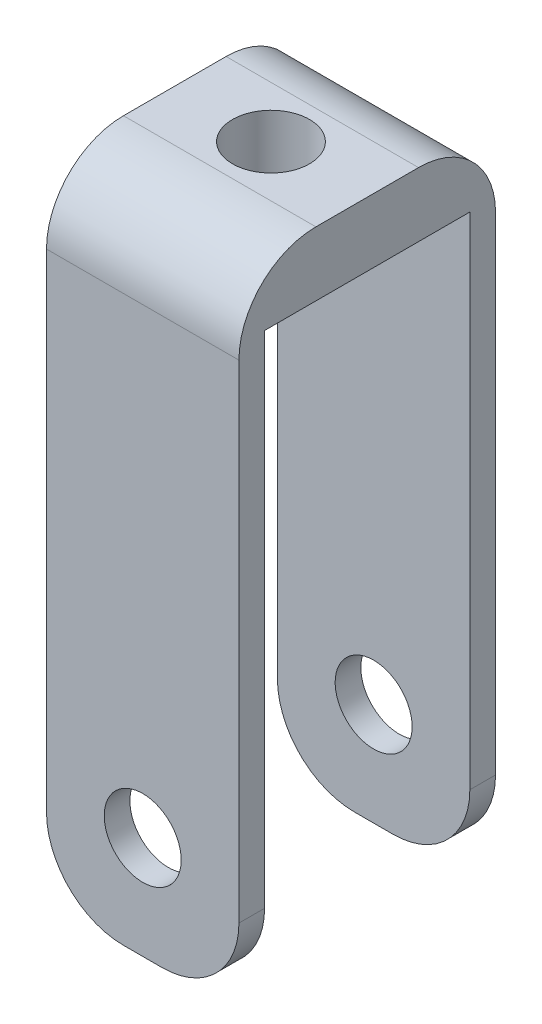
SolidWorks part; units mm, degrees
ref_plane "Front Plane" through (0, 0, 0) normal (0, 0, 1) x (1, 0, 0)
ref_plane "Top Plane" through (0, 0, 0) normal (0, 1, 0) x (1, 0, 0)
ref_plane "Right Plane" through (0, 0, 0) normal (1, 0, 0) x (0, 0, -1)
sketch "Sketch1" plane through (0, 0, 0) normal (1, 0, 0) x (0, 0, -1)
  line L0 (0, 0) -> (-10, 0)
  line L1 (-10, 0) -> (-10, -50)
  line L2 (-10, -50) -> (-8, -50)
  line L3 (-8, -50) -> (-8, -5)
  line L4 (-8, -5) -> (8, -5)
  line L5 (8, -5) -> (8, -50)
  line L6 (8, -50) -> (10, -50)
  line L7 (10, -50) -> (10, 0)
  line L8 (0, 0) -> (10, 0)
  dimension "D1" = 10
  dimension "D3" = 5
  dimension "D4" = 2
  dimension "D6" = 45
  dimension "D5" = 2
  dimension "D7" = 45
  dimension "D2" = 10
extrude "Boss-Extrude1" add sketch "Sketch1" along normal mid plane 15
sketch "Sketch2" plane through (0, 0, 0) normal (0, 1, 0) x (1, 0, 0)
  circle A0 centre (0, 0) radius 3
  dimension "D1" = 6
extrude "Cut-Extrude1" cut sketch "Sketch2" against normal blind 15
sketch "Sketch3" plane through (0, 0, 10) normal (0, 0, 1) x (1, 0, 0)
  line L0 (7.5, 0) -> (-7.5, 0) construction
  circle A0 centre (0, -42) radius 3
  dimension "D1" = 6
  dimension "D2" = 42
extrude "Cut-Extrude2" cut sketch "Sketch3" against normal through all
fillet "Fillet1" radius 6 6 edges at (0, 0, -10) (0, 0, 10) (-7.5, -50, 9) (-7.5, -50, -9) (7.5, -50, -9) (7.5, -50, 9)
equation "\"D5@Sketch1\"=\"D4@Sketch1\""
equation "\"D7@Sketch1\"=\"D6@Sketch1\""
equation "\"D2@Sketch1\"=\"D1@Sketch1\""
